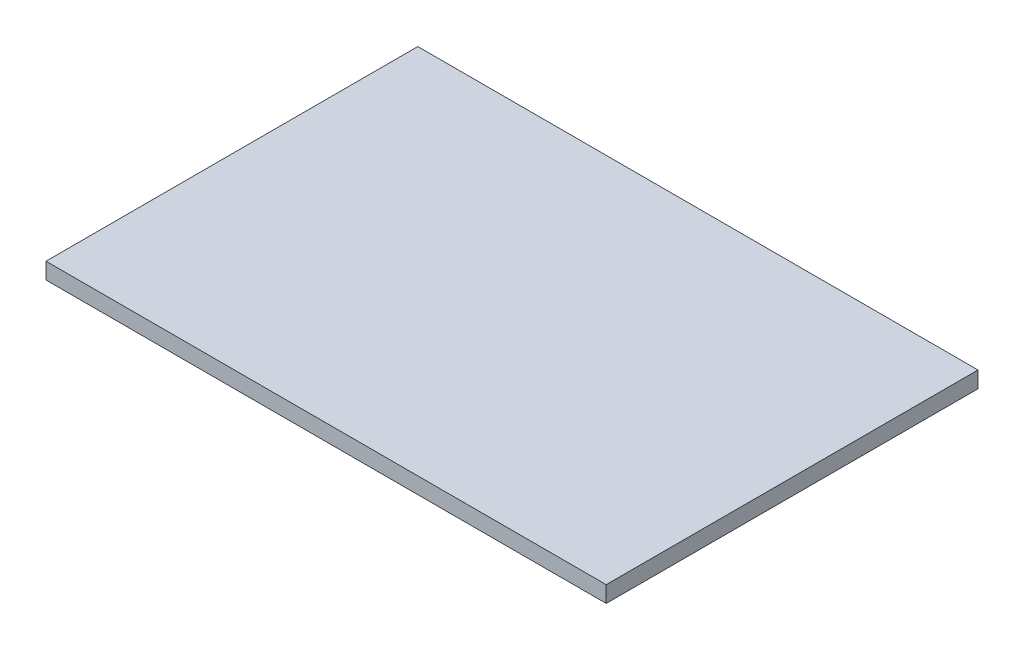
SolidWorks part; units mm, degrees
ref_plane "Płaszczyzna przednia" through (0, 0, 0) normal (0, 0, 1) x (1, 0, 0)
ref_plane "Płaszczyzna górna" through (0, 0, 0) normal (0, 1, 0) x (1, 0, 0)
ref_plane "Płaszczyzna prawa" through (0, 0, 0) normal (1, 0, 0) x (0, 0, -1)
sketch "Szkic1" plane through (0, 0, 0) normal (0, 1, 0) x (1, 0, 0)
  line L1 (-275, -182.5) -> (275, -182.5)
  line L2 (-275, -182.5) -> (-275, 182.5)
  line L3 (-275, 182.5) -> (275, 182.5)
  line L4 (275, -182.5) -> (275, 182.5)
  line L5 (-275, -182.5) -> (275, 182.5) construction
  line L6 (-275, 182.5) -> (275, -182.5) construction
  point P0 (0, 0)
  dimension "D1" = 550
  dimension "D2" = 365
extrude "Dodanie-wyciągnięcie1" add sketch "Szkic1" along normal blind 16
